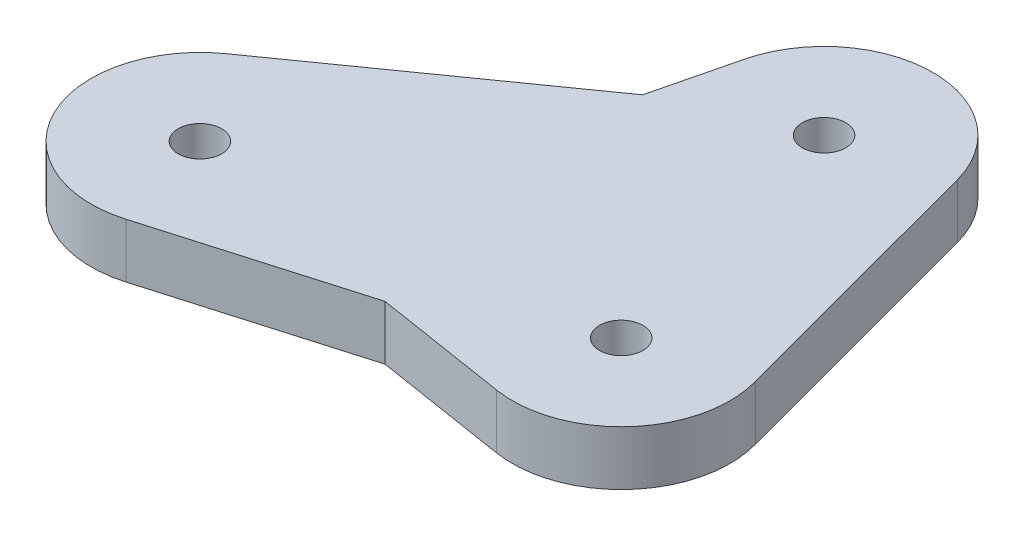
SolidWorks part; units mm, degrees
ref_plane "Ebene vorne" through (0, 0, 0) normal (0, 0, 1) x (1, 0, 0)
ref_plane "Ebene oben" through (0, 0, 0) normal (0, 1, 0) x (1, 0, 0)
ref_plane "Ebene rechts" through (0, 0, 0) normal (1, 0, 0) x (0, 0, -1)
sketch "Skizze1" plane through (0, 0, 0) normal (0, 1, 0) x (1, 0, 0)
  line L0 (20.9847, -13.3576) -> (8.8011, -11.4232)
  line L7 (32.1749, -0.7587) -> (20.9847, -13.3576)
  line L8 (8.8011, -11.4232) -> (-9.6548, -16.7905)
  line L10 (4.1937, 16.8424) -> (6.0339, 24.3446)
  line L11 (32.1749, -0.7587) -> (25.4064, 24.5462)
  line L12 (25.4064, 24.5462) -> (6.0339, 24.3446)
  line L15 (4.1937, 16.8424) -> (-18.2248, 0.9739)
  line L16 (-18.2248, 0.9739) -> (-9.6548, -16.7905)
  circle A0 centre (-12.4473, -7.1883) radius 10
  circle A1 centre (15.746, 21.9623) radius 10
  circle A2 centre (22.5527, -3.4813) radius 10
  circle A3 centre (-12.4473, -7.1883) radius 2
  circle A4 centre (22.5527, -3.4813) radius 2
  circle A5 centre (15.746, 21.9623) radius 2
  dimension "D1" = 20
  dimension "D2" = 20
  dimension "D3" = 20
  dimension "D4" = 35
  dimension "D5" = 4
  dimension "D6" = 4
  dimension "D7" = 4
extrude "Aufsatz-Linear austragen1" add sketch "Skizze1" along normal blind 5
